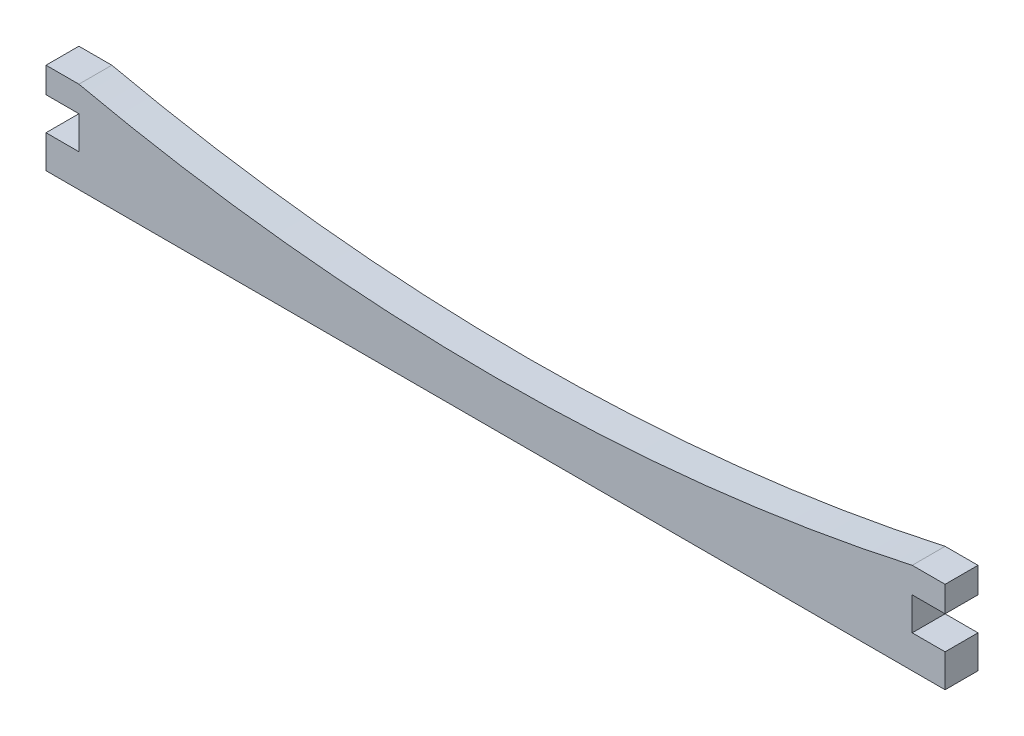
SolidWorks part; units mm, degrees
ref_plane "Front Plane" through (0, 0, 0) normal (0, 0, 1) x (1, 0, 0)
ref_plane "Top Plane" through (0, 0, 0) normal (0, 1, 0) x (1, 0, 0)
ref_plane "Right Plane" through (0, 0, 0) normal (1, 0, 0) x (0, 0, -1)
sketch "Sketch1" plane through (0, 0, 0) normal (0, 0, 1) x (1, 0, 0)
  line L0 (-123, 0) -> (123, 0)
  line L1 (-123, 0) -> (-123, 25)
  line L3 (123, 25) -> (123, 0)
  line L4 (-114, 25) -> (-114, 0) construction
  line L5 (114, 25) -> (114, 0) construction
  line L6 (-123, 25) -> (-114, 25)
  line L7 (123, 25) -> (114, 25)
  line L8 (-114, 25) -> (114, 25) construction
  line L9 (-114, 12.5) -> (114, 12.5) construction
  circle A0 centre (0, 538.59) radius 526.09
  dimension "D1" = 246
  dimension "D2" = 25
  dimension "D3" = 9
  dimension "D4" = 9
extrude "Boss-Extrude2" add sketch "Sketch1" along normal blind 9 contours A0 L6 L1 L0 L3 L7
sketch "Sketch2" plane through (0, 0, 0) normal (0, 0, 1) x (1, 0, 0)
  line L0 (123, 25) -> (123, 0) construction
  line L1 (123, 18) -> (114, 18)
  line L2 (123, 18) -> (123, 9)
  line L3 (123, 9) -> (114, 9)
  line L4 (114, 18) -> (114, 9)
  line L7 (118.5, 25) -> (118.5, 18) construction
  line L9 (123, 25) -> (114, 25) construction
  line L10 (118.5, 18) -> (118.5, 9) construction
  line L11 (118.5, 9) -> (118.5, 0) construction
  line L12 (-123, 0) -> (123, 0) construction
  line L13 (0, 0) -> (0, 12.5) construction
  line L14 (-118.5, 9) -> (-118.5, 0) construction
  line L15 (-118.5, 18) -> (-118.5, 9) construction
  line L16 (-118.5, 25) -> (-118.5, 18) construction
  line L17 (-114, 18) -> (-114, 9)
  line L18 (-123, 9) -> (-114, 9)
  line L19 (-123, 18) -> (-123, 9)
  line L20 (-123, 18) -> (-114, 18)
  arc A0 (-114, 25) -> (114, 25) centre (0, 538.59) ccw construction
  dimension "D1" = 9
  dimension "D2" = 9
  dimension "D3" = 9
extrude "Cut-Extrude1" cut sketch "Sketch2" along normal through all
